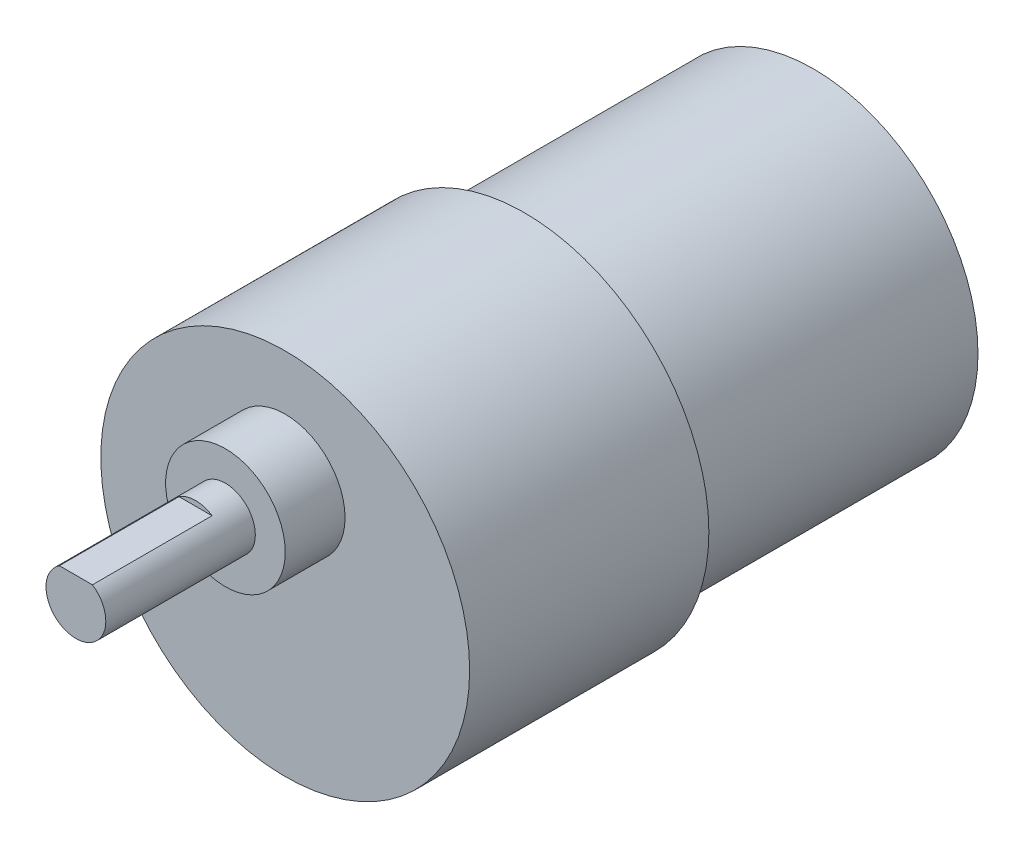
SolidWorks part; units mm, degrees
ref_plane "Ebene vorne" through (0, 0, 0) normal (1, 0, 0) x (0, 1, 0)
ref_plane "Ebene oben" through (0, 0, 0) normal (0, 0, 1) x (0, 1, 0)
ref_plane "Ebene rechts" through (0, 0, 0) normal (0, 1, 0) x (-1, 0, 0)
sketch "Skizze1" plane through (0, 0, 0) normal (0, 0, 1) x (0, 1, 0)
  circle A0 centre (0, 0) radius 16.5
  dimension "D1" = 33
extrude "Aufsatz-Linear austragen1" add sketch "Skizze1" along normal blind 29
sketch "Skizze2" plane through (0, 0, 29) normal (0, 0, 1) x (1, 0, 0)
  circle A0 centre (0, 0) radius 18.5
  dimension "D1" = 37
extrude "Aufsatz-Linear austragen2" add sketch "Skizze2" along normal blind 24 separate body
sketch "Skizze3" plane through (0, 0, 53) normal (0, 0, 1) x (1, 0, 0)
  line L0 (0, 0) -> (0, 7) construction
  circle A0 centre (0, 7) radius 6
  dimension "D2" = 12
  dimension "D1" = 7
extrude "Aufsatz-Linear austragen3" add sketch "Skizze3" along normal blind 6 separate body
sketch "Skizze4" plane through (0, 0, 59) normal (0, 0, 1) x (1, 0, 0)
  circle A0 centre (0, 7) radius 3
  dimension "D1" = 6
extrude "Aufsatz-Linear austragen4" add sketch "Skizze4" along normal blind 15 separate body
sketch "Skizze5" plane through (0, 0, 74) normal (0, 0, 1) x (1, 0, 0)
  line L1 (-2.809, 11.7554) -> (3.1751, 11.7554)
  line L2 (-2.809, 11.7554) -> (-2.809, 9.5)
  line L3 (-2.809, 9.5) -> (3.1751, 9.5)
  line L4 (3.1751, 11.7554) -> (3.1751, 9.5)
  circle A0 centre (0, 7) radius 3 construction
  dimension "D1" = 2.5
extrude "Schnitt-Linear austragen1" cut sketch "Skizze5" against normal blind 12
